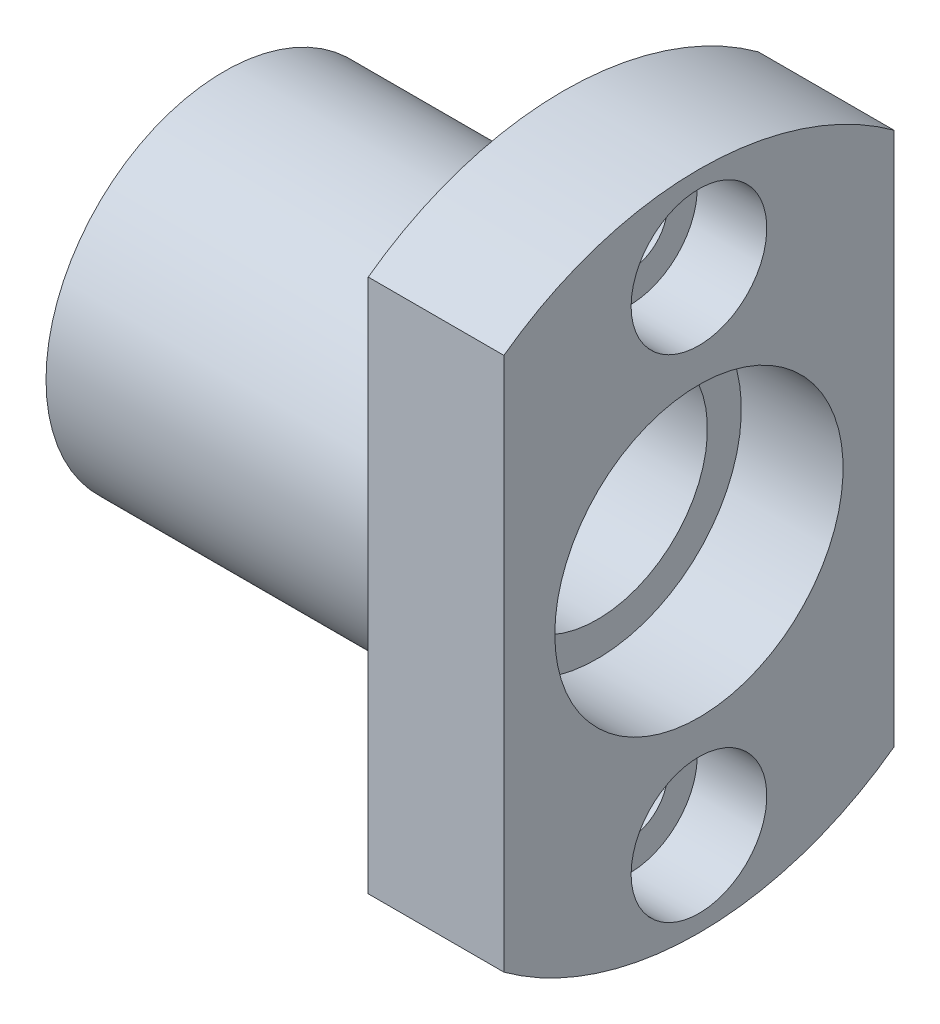
SolidWorks part; units mm, degrees
ref_plane "正面" through (0, 0, 0) normal (0, 0, 1) x (1, 0, 0)
ref_plane "平面" through (0, 0, 0) normal (0, 1, 0) x (1, 0, 0)
ref_plane "右側面" through (0, 0, 0) normal (1, 0, 0) x (0, 0, -1)
ref_plane "平面1" through (0, 0, 0) normal (0, 0, 1) x (1, 0, 0)
sketch "ｽｹｯﾁ1" plane through (0, 0, 0) normal (0, 0, 1) x (1, 0, 0)
  line L0 (-28, 8.5) -> (-22, 8.5)
  line L1 (-22, 8.5) -> (-22, 6.5)
  line L2 (-22, 6.5) -> (-6, 6.5)
  line L3 (-6, 6.5) -> (-6, 8.5)
  line L4 (-6, 8.5) -> (0, 8.5)
  line L5 (0, 8.5) -> (0, 19.5)
  line L6 (0, 19.5) -> (-8, 19.5)
  line L7 (-8, 19.5) -> (-8, 10.5)
  line L8 (-8, 10.5) -> (-28, 10.5)
  line L9 (-28, 10.5) -> (-28, 8.5)
  line L10 (0, 0) -> (-28, 0) construction
revolve "回転1" add sketch "ｽｹｯﾁ1" angle 360 about L10
ref_plane "平面2" through (0, 0, 0) normal (0, 0, 1) x (1, 0, 0)
sketch "ｽｹｯﾁ2" plane through (0, 0, 0) normal (0, 0, 1) x (1, 0, 0)
  line L0 (-8, 14.5) -> (-8, 16.75)
  line L1 (-8, 16.75) -> (-4.1, 16.75)
  line L2 (-4.1, 16.75) -> (-4.1, 18.5)
  line L3 (-4.1, 18.5) -> (0, 18.5)
  line L4 (0, 18.5) -> (0, 14.5)
  line L5 (0, 14.5) -> (-8, 14.5)
  line L6 (0, 14.5) -> (-8, 14.5) construction
revolve "ｶｯﾄ - 回転1" cut sketch "ｽｹｯﾁ2" angle 360 about L6
ref_plane "平面3" through (0, 0, 0) normal (0, 0, 1) x (1, 0, 0)
sketch "ｽｹｯﾁ3" plane through (0, 0, 0) normal (0, 0, 1) x (1, 0, 0)
  line L0 (-8, -14.5) -> (-8, -12.25)
  line L1 (-8, -12.25) -> (-4.1, -12.25)
  line L2 (-4.1, -12.25) -> (-4.1, -10.5)
  line L3 (-4.1, -10.5) -> (0, -10.5)
  line L4 (0, -10.5) -> (0, -14.5)
  line L5 (0, -14.5) -> (-8, -14.5)
  line L6 (0, -14.5) -> (-8, -14.5) construction
revolve "ｶｯﾄ - 回転2" cut sketch "ｽｹｯﾁ3" angle 360 about L6
ref_plane "平面4" through (0, 0, 0) normal (1, 0, 0) x (0, 0, -1)
sketch "ｽｹｯﾁ4" plane through (0, 0, 0) normal (1, 0, 0) x (0, 0, -1)
  line L0 (-11.5, 19.5) -> (-11.5, -19.5)
  line L1 (-11.5, -19.5) -> (11.5, -19.5)
  line L2 (11.5, -19.5) -> (11.5, 19.5)
  line L3 (11.5, 19.5) -> (-11.5, 19.5)
  circle A0 centre (0, 0) radius 100
extrude "ｶｯﾄ - 押し出し1" cut sketch "ｽｹｯﾁ4" against normal blind 8
